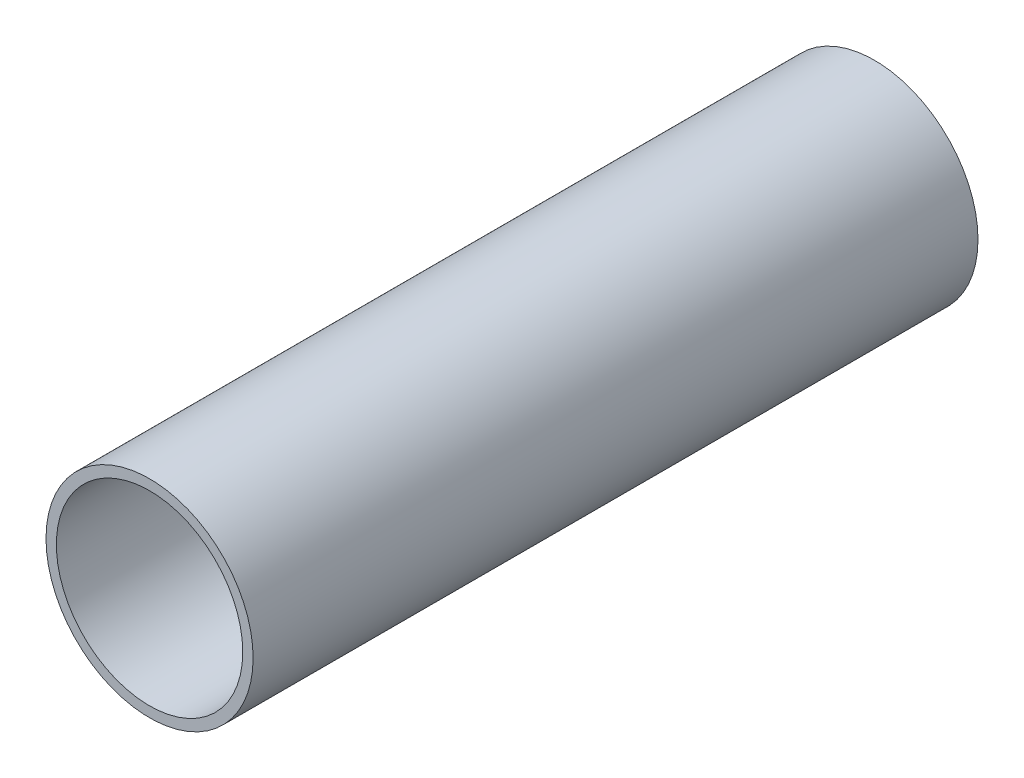
SolidWorks part; units mm, degrees
ref_plane "Front Plane" through (0, 0, 0) normal (0, 0, 1) x (1, 0, 0)
ref_plane "Top Plane" through (0, 0, 0) normal (0, 1, 0) x (1, 0, 0)
ref_plane "Right Plane" through (0, 0, 0) normal (1, 0, 0) x (0, 0, -1)
sketch "Sketch1" plane through (0, 0, 0) normal (0, 0, 1) x (1, 0, 0)
  circle A0 centre (0, 0) radius 1.8
  circle A1 centre (0, 0) radius 2
  dimension "D1" = 4
  dimension "D2" = 3.6
extrude "Boss-Extrude1" add sketch "Sketch1" along normal blind 14
